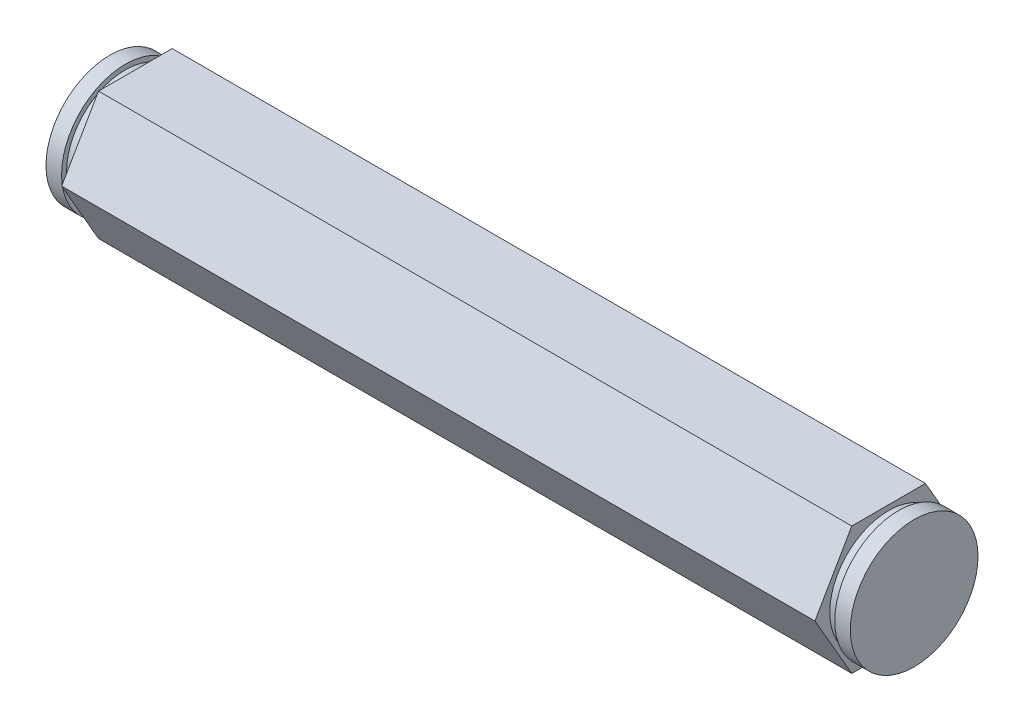
SolidWorks part; units mm, degrees
material "7075-T6 (SN)"
ref_plane "Front Plane" through (0, 0, 0) normal (0, 0, 1) x (1, 0, 0)
ref_plane "Top Plane" through (0, 0, 0) normal (0, 1, 0) x (1, 0, 0)
ref_plane "Right Plane" through (0, 0, 0) normal (1, 0, 0) x (0, 0, -1)
sketch "Sketch1" plane through (0, 0, 0) normal (1, 0, 0) x (0, 0, -1)
  line L1 (7.3323, 0) -> (3.6662, 6.35)
  line L2 (3.6662, 6.35) -> (-3.6662, 6.35)
  line L3 (-3.6662, 6.35) -> (-7.3323, 0)
  line L4 (-7.3323, 0) -> (-3.6662, -6.35)
  line L5 (-3.6662, -6.35) -> (3.6662, -6.35)
  line L6 (3.6662, -6.35) -> (7.3323, 0)
  circle A0 centre (0, 0) radius 6.35 construction
  dimension "D1" = 12.7
extrude "Boss-Extrude1" add sketch "Sketch1" along normal mid plane 80.01
sketch "Sketch2" plane through (0, 0, 0) normal (0, 1, 0) x (1, 0, 0)
  line L0 (37.465, -5.8547) -> (38.4556, -5.8547)
  line L1 (38.4556, -5.8547) -> (38.4556, -6.35)
  line L2 (38.4556, -6.35) -> (40.005, -6.35)
  line L3 (40.005, -6.35) -> (40.005, -8.89)
  line L4 (40.005, -8.89) -> (37.465, -8.89)
  line L5 (37.465, -8.89) -> (37.465, -5.8547)
  line L6 (0, 0) -> (49.5443, 0) construction
  dimension "D1" = 2.54
  dimension "D2" = 6.35
  dimension "D3" = 5.8547
  dimension "D4" = 2.54
  dimension "D5" = 0.9906
revolve "Cut-Revolve1" cut sketch "Sketch2" angle 360 about L6
mirror "Mirror1" about plane through (0, 0, 0) normal (1, 0, 0) of "Cut-Revolve1"
